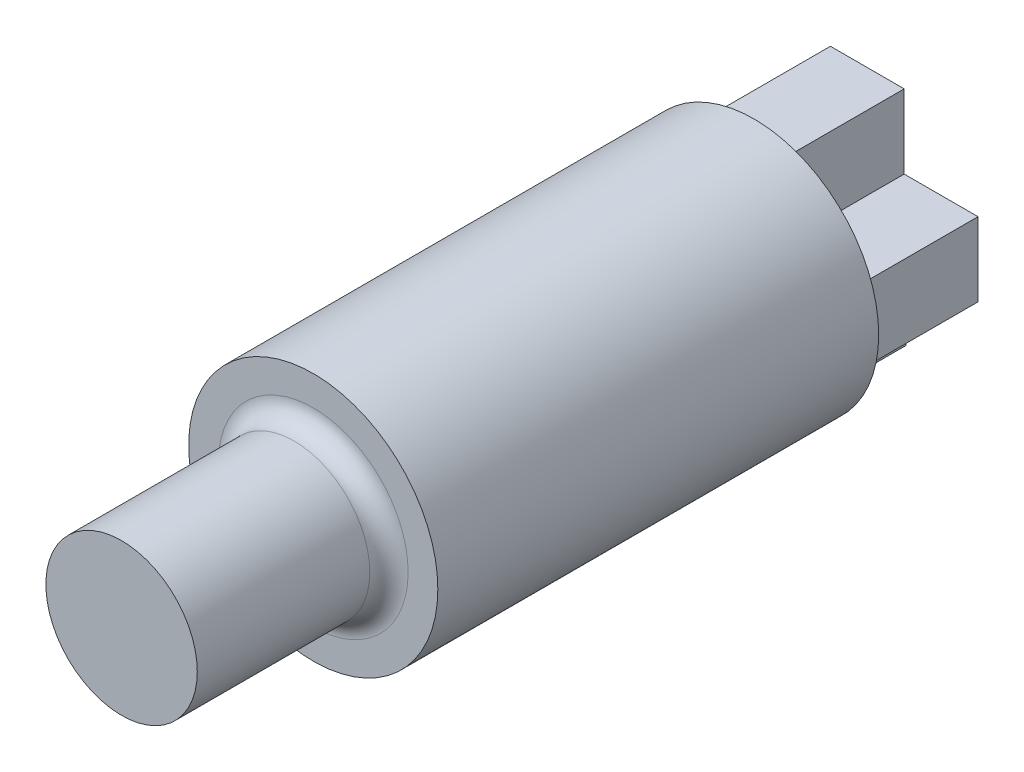
SolidWorks part; units mm, degrees
ref_plane "Alzado" through (0, 0, 0) normal (0, 0, 1) x (1, 0, 0)
ref_plane "Planta" through (0, 0, 0) normal (0, 1, 0) x (1, 0, 0)
ref_plane "Vista lateral" through (0, 0, 0) normal (1, 0, 0) x (0, 0, -1)
sketch "Croquis1" plane through (0, 0, 0) normal (0, 0, 1) x (1, 0, 0)
  circle A0 centre (0, 0) radius 6.5
  dimension "D1" = 13
extrude "Saliente-Extruir1" add sketch "Croquis1" along normal blind 23
sketch "Croquis2" plane through (0, 0, 23) normal (0, 0, 1) x (1, 0, 0)
  circle A0 centre (0, 0) radius 3.95
  dimension "D1" = 7.9
extrude "Saliente-Extruir2" add sketch "Croquis2" along normal blind 10
fillet "Redondeo1" radius 1 1 edges at (3.95, 0, 23)
sketch "Croquis3" plane through (0, 0, 0) normal (0, 0, -1) x (-1, 0, 0)
  line L0 (-1.8307, 5.775) -> (2.0193, 5.775)
  line L1 (2.0193, 5.775) -> (2.0193, 1.925)
  line L2 (2.0193, 1.925) -> (5.775, 1.925)
  line L3 (5.775, 1.925) -> (5.775, -1.925)
  line L4 (5.775, -1.925) -> (1.925, -1.925)
  line L5 (1.925, -1.925) -> (1.925, -5.775)
  line L6 (1.925, -5.775) -> (-1.925, -5.775)
  line L7 (-1.925, -5.775) -> (-1.925, -1.925)
  line L8 (-1.925, -1.925) -> (-5.6807, -1.925)
  line L9 (-5.6807, -1.925) -> (-5.6807, 1.925)
  line L10 (-5.6807, 1.925) -> (-1.8307, 1.925)
  line L11 (-1.8307, 1.925) -> (-1.8307, 5.775)
  dimension "D1" = 3.85
  dimension "D2" = 3.85
  dimension "D3" = 3.85
  dimension "D4" = 3.85
  dimension "D5" = 3.85
  dimension "D6" = 3.85
  dimension "D7" = 3.85
  dimension "D8" = 3.85
  dimension "D9" = 3.85
  dimension "D10" = 1.925
  dimension "D11" = 1.925
extrude "Saliente-Extruir3" add sketch "Croquis3" along normal blind 6
